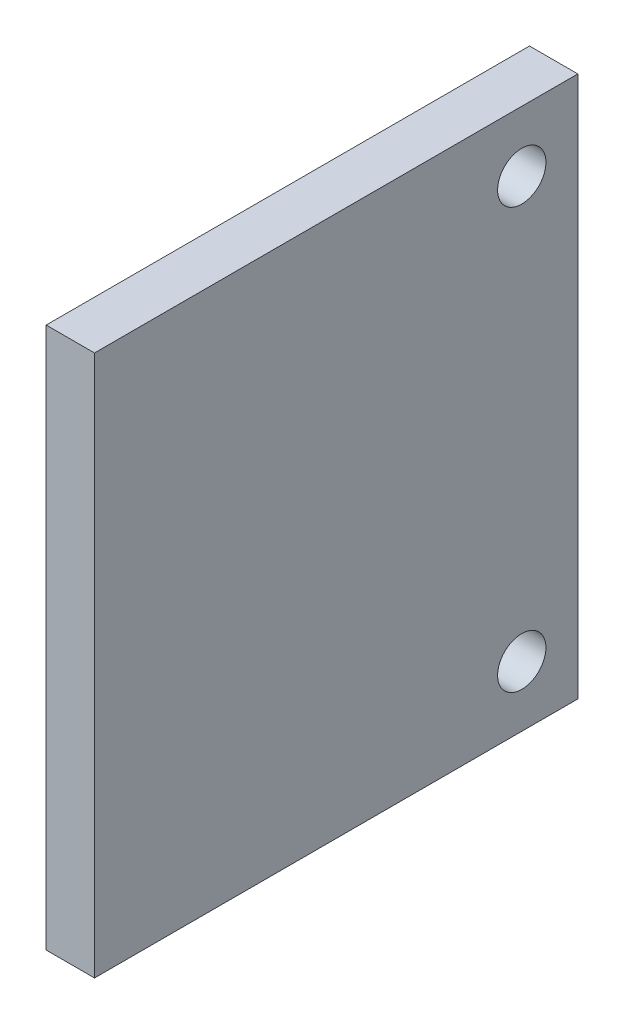
SolidWorks part; units mm, degrees
ref_plane "Ön Düzlem" through (0, 0, 0) normal (1, 0, 0) x (0, 1, 0)
ref_plane "Üst Düzlem" through (0, 0, 0) normal (0, 0, 1) x (0, 1, 0)
ref_plane "Sağ Düzlem" through (0, 0, 0) normal (0, 1, 0) x (-1, 0, 0)
sketch "Çizim1" plane through (0, 0, 0) normal (1, 0, 0) x (0, 1, 0)
  line L5 (-14, -2.9) -> (14, -2.9)
  line L6 (-14, -2.9) -> (-14, 22.1)
  line L7 (-14, 22.1) -> (14, 22.1)
  line L8 (14, -2.9) -> (14, 22.1)
  circle A0 centre (-10.87, 0) radius 1.25
  circle A1 centre (10.87, 0) radius 1.25
  point P4 (0, 0)
  point P6 (14.304, 17.7657)
  point P10 (-20.0444, 22.1)
  point P11 (0, -2.9)
  dimension "D1" = 21.74
  dimension "D3" = 2.5
  dimension "D2" = 10.87
  dimension "D4" = 28
  dimension "D5" = 22.1
  dimension "D6" = 25
extrude "Yükseklik-Ekstrüzyon1" add sketch "Çizim1" along normal blind 2.5
